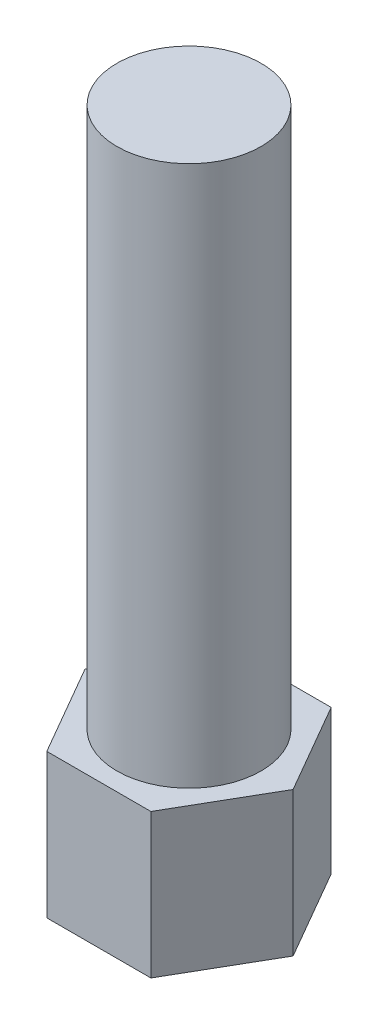
SolidWorks part; units mm, degrees
ref_plane "Ön Düzlem" through (0, 0, 0) normal (0, 0, 1) x (1, 0, 0)
ref_plane "Üst Düzlem" through (0, 0, 0) normal (0, 1, 0) x (1, 0, 0)
ref_plane "Sağ Düzlem" through (0, 0, 0) normal (1, 0, 0) x (0, 0, -1)
sketch "Sketch1" plane through (0, 0, 0) normal (0, 1, 0) x (1, 0, 0)
  line L1 (2.8868, 0) -> (1.4434, 2.5)
  line L2 (1.4434, 2.5) -> (-1.4434, 2.5)
  line L3 (-1.4434, 2.5) -> (-2.8868, 0)
  line L4 (-2.8868, 0) -> (-1.4434, -2.5)
  line L5 (-1.4434, -2.5) -> (1.4434, -2.5)
  line L6 (1.4434, -2.5) -> (2.8868, 0)
  circle A0 centre (0, 0) radius 2.5 construction
  dimension "D1" = 5
extrude "Boss-Extrude1" add sketch "Sketch1" along normal blind 4
sketch "Sketch2" plane through (0, 4, 0) normal (0, 1, 0) x (1, 0, 0)
  circle A0 centre (0, 0) radius 2
  dimension "D1" = 4
extrude "Boss-Extrude2" add sketch "Sketch2" along normal blind 15
